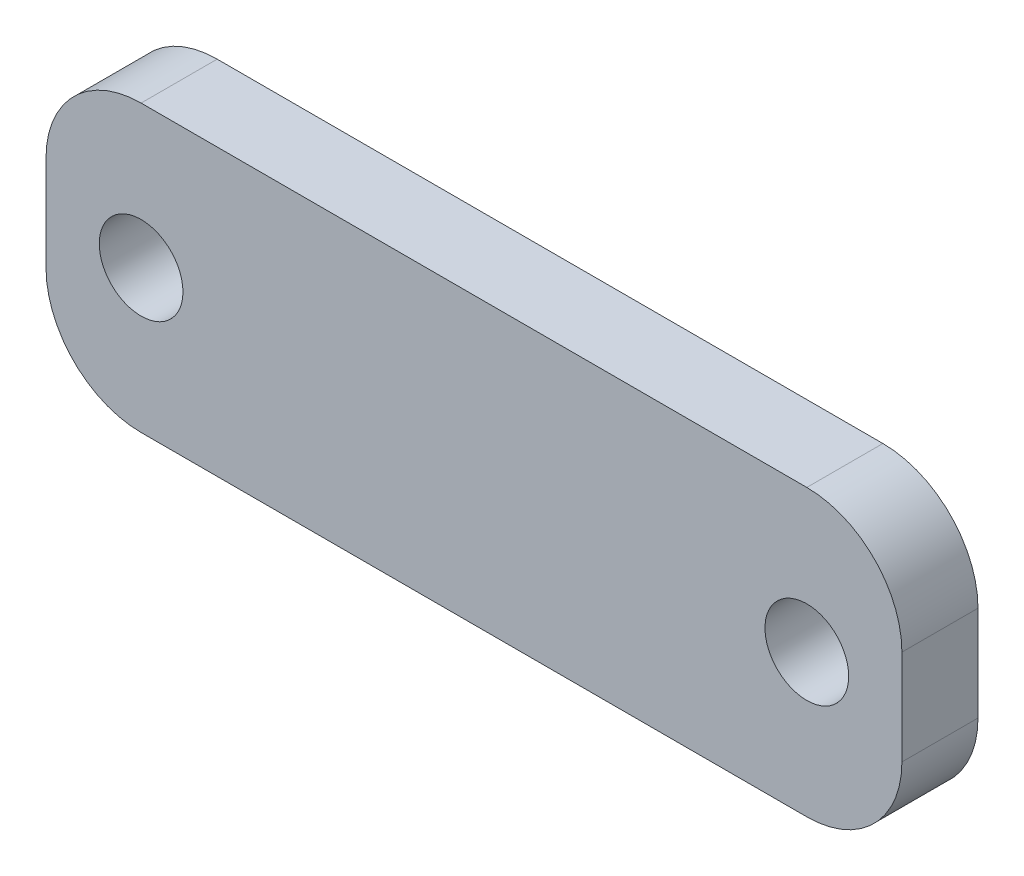
SolidWorks part; units mm, degrees
ref_plane "Alzado" through (0, 0, 0) normal (0, 0, 1) x (1, 0, 0)
ref_plane "Planta" through (0, 0, 0) normal (0, 1, 0) x (1, 0, 0)
ref_plane "Vista lateral" through (0, 0, 0) normal (1, 0, 0) x (0, 0, -1)
sketch "Croquis1" plane through (0, 0, 0) normal (0, 0, 1) x (1, 0, 0)
  line L0 (0, 0) -> (0, 15)
  line L1 (0, 15) -> (45, 15)
  line L2 (45, 15) -> (45, 0)
  line L3 (45, 0) -> (0, 0)
  circle A0 centre (5, 7.5) radius 2.2
  circle A1 centre (40, 7.5) radius 2.2
extrude "Saliente-Extruir1" add sketch "Croquis1" along normal blind 4
fillet "Redondeo1" radius 5 4 edges at (0, 0, 2) (0, 15, 2) (45, 0, 2) (45, 15, 2)
